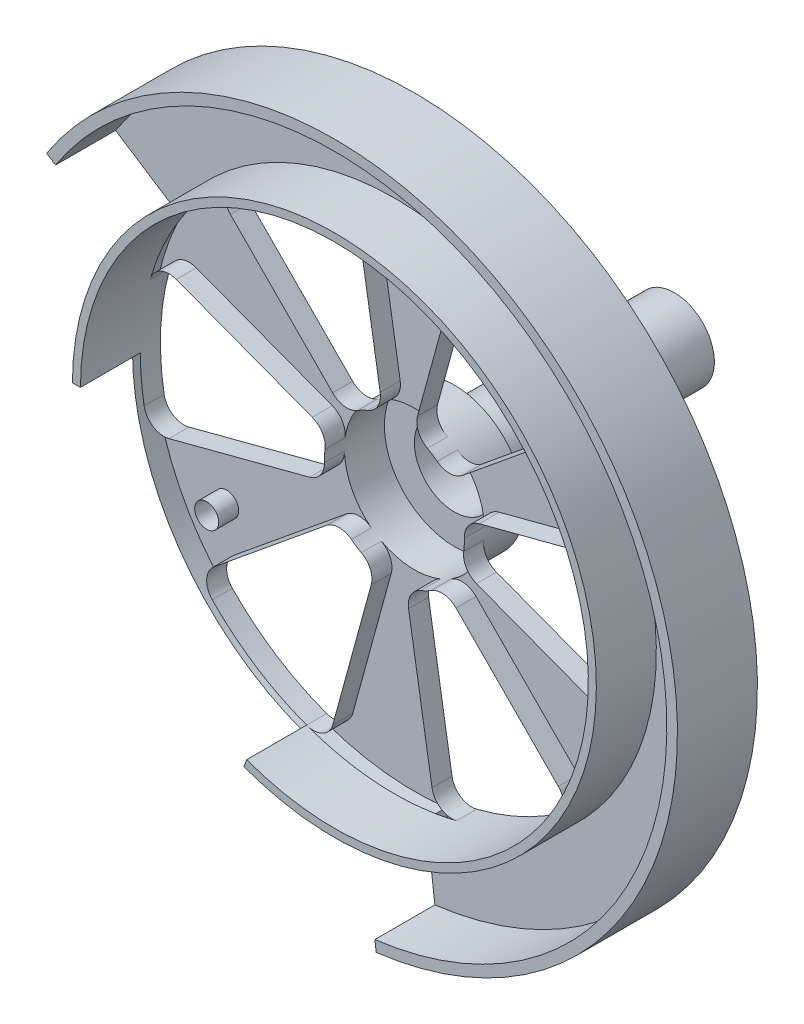
SolidWorks part; units mm, degrees
ref_plane "Piano frontale" through (0, 0, 0) normal (0, 0, 1) x (1, 0, 0)
ref_plane "Piano superiore" through (0, 0, 0) normal (0, 1, 0) x (1, 0, 0)
ref_plane "Piano destro" through (0, 0, 0) normal (1, 0, 0) x (0, 0, -1)
sketch "Schizzo2" plane through (0, 0, 0) normal (0, 0, 1) x (1, 0, 0)
  circle A0 centre (0, 0) radius 65.5
  dimension "D1" = 131
extrude "Estrusione-Estrusione1" add sketch "Schizzo2" along normal blind 5
sketch "Schizzo3" plane through (0, 0, 5) normal (0, 0, 1) x (1, 0, 0)
  line L0 (0, 65.5) -> (0, -65.5) construction
  line L1 (-63.5, 0) -> (0, 0) construction
  line L3 (0, 0) -> (65.5, 0) construction
  line L7 (-3.5452, 21.6491) -> (-9.4192, 57.5198)
  line L8 (-15.4307, 15.5931) -> (-40.998, 41.4296)
  line L9 (-9.4192, 57.5198) -> (0, 0) construction
  line L10 (-40.998, 41.4296) -> (0, 0) construction
  line L11 (5.7887, 21.1599) -> (15.3801, 56.2201)
  line L12 (16.9761, 13.8947) -> (45.104, 36.9172)
  line L13 (21.2194, 5.5668) -> (56.3781, 14.7905)
  line L14 (20.5212, -7.7543) -> (54.5232, -20.6026)
  line L15 (15.4307, -15.5931) -> (40.998, -41.4296)
  line L16 (3.5452, -21.6491) -> (9.4192, -57.5198)
  line L17 (-5.7887, -21.1599) -> (-15.3801, -56.2201)
  line L18 (-16.9761, -13.8947) -> (-45.104, -36.9172)
  line L19 (-21.2194, -5.5668) -> (-56.3781, -14.7905)
  line L20 (-20.5212, 7.7543) -> (-54.5232, 20.6026)
  circle A6 centre (0, 0) radius 65.5 construction
  arc A9 (-6.5951, 16.2097) -> (-9.2374, 14.8634) centre (0, 0) ccw
  arc A11 (-40.998, 41.4296) -> (-40.6444, 48.7882) centre (-37.444, 44.9466) cw
  arc A12 (-15.5803, 61.5589) -> (-9.4192, 57.5198) centre (-14.3535, 56.7118) cw
  arc A13 (-9.2374, 14.8634) -> (-15.4307, 15.5931) centre (-11.8767, 19.1101) cw
  arc A14 (-6.5951, 16.2097) -> (-3.5452, 21.6491) centre (-8.4794, 20.841) ccw
  arc A15 (45.5215, 44.2724) -> (45.104, 36.9172) centre (41.9371, 40.7864) cw
  arc A16 (21.9296, 59.5931) -> (45.5215, 44.2724) centre (0, 0) cw
  arc A17 (15.3801, 56.2201) -> (21.9296, 59.5931) centre (20.2029, 54.9008) cw
  arc A18 (10.7404, 13.8164) -> (8.2534, 15.4315) centre (0, 0) ccw
  arc A19 (8.2534, 15.4315) -> (5.7887, 21.1599) centre (10.6115, 19.8405) cw
  arc A20 (10.7404, 13.8164) -> (16.9761, 13.8947) centre (13.8091, 17.7639) ccw
  arc A21 (61.1018, -17.2865) -> (54.5232, -20.6026) centre (56.2906, -15.9254) cw
  arc A22 (62.574, 10.805) -> (61.1018, -17.2865) centre (0, 0) cw
  arc A23 (56.3781, 14.7905) -> (62.574, 10.805) centre (57.6469, 9.9542) cw
  arc A24 (17.3356, -2.3933) -> (17.4908, 0.5681) centre (0, 0) ccw
  arc A25 (17.4908, 0.5681) -> (21.2194, 5.5668) centre (22.4881, 0.7305) cw
  arc A26 (17.3356, -2.3933) -> (20.5212, -7.7543) centre (22.2886, -3.0771) ccw
  arc A27 (15.5803, -61.5589) -> (9.4192, -57.5198) centre (14.3535, -56.7118) cw
  arc A28 (40.6444, -48.7882) -> (15.5803, -61.5589) centre (0, 0) cw
  arc A29 (40.998, -41.4296) -> (40.6444, -48.7882) centre (37.444, -44.9466) cw
  arc A30 (6.5951, -16.2097) -> (9.2374, -14.8634) centre (0, 0) ccw
  arc A31 (9.2374, -14.8634) -> (15.4307, -15.5931) centre (11.8767, -19.1101) cw
  arc A32 (6.5951, -16.2097) -> (3.5452, -21.6491) centre (8.4794, -20.841) ccw
  arc A33 (-45.5215, -44.2724) -> (-45.104, -36.9172) centre (-41.9371, -40.7864) cw
  arc A34 (-21.9296, -59.5931) -> (-45.5215, -44.2724) centre (0, 0) cw
  arc A35 (-15.3801, -56.2201) -> (-21.9296, -59.5931) centre (-20.2029, -54.9008) cw
  arc A36 (-10.7404, -13.8164) -> (-8.2534, -15.4315) centre (0, 0) ccw
  arc A37 (-8.2534, -15.4315) -> (-5.7887, -21.1599) centre (-10.6115, -19.8405) cw
  arc A38 (-10.7404, -13.8164) -> (-16.9761, -13.8947) centre (-13.8091, -17.7639) ccw
  arc A39 (-61.1018, 17.2865) -> (-54.5232, 20.6026) centre (-56.2906, 15.9254) cw
  arc A40 (-62.574, -10.805) -> (-61.1018, 17.2865) centre (0, 0) cw
  arc A41 (-56.3781, -14.7905) -> (-62.574, -10.805) centre (-57.6469, -9.9542) cw
  arc A42 (-17.3356, 2.3933) -> (-17.4908, -0.5681) centre (0, 0) ccw
  arc A43 (-17.4908, -0.5681) -> (-21.2194, -5.5668) centre (-22.4881, -0.7305) cw
  arc A44 (-17.3356, 2.3933) -> (-20.5212, 7.7543) centre (-22.2886, 3.0771) ccw
  arc A45 (-61.1018, 17.2865) -> (-62.574, -10.805) centre (0, 0) ccw
  arc A46 (-15.5803, 61.5589) -> (-40.6444, 48.7882) centre (0, 0) ccw
  arc A47 (45.5215, 44.2724) -> (21.9296, 59.5931) centre (0, 0) ccw
  arc A48 (61.1018, -17.2865) -> (62.574, 10.805) centre (0, 0) ccw
  arc A49 (15.5803, -61.5589) -> (40.6444, -48.7882) centre (0, 0) ccw
  arc A50 (-45.5215, -44.2724) -> (-21.9296, -59.5931) centre (0, 0) ccw
  dimension "D1" = 35
  dimension "D4" = 5
  dimension "D5" = 5
  dimension "D6" = 5
  dimension "D7" = 5
  dimension "D8" = 6
  dimension "D3" = 35.4
  dimension "D9" = 127
  dimension "D2" = 9.3
extrude "Taglio-Estrusione1" cut sketch "Schizzo3" against normal blind 5 contours A12 A46 A11 L8 A13 A9 A14 L7 | A18 A20 L12 A15 A16 A17 L11 A19 | A24 A26 L14 A21 A22 A23 L13 A25 | A30 A32 L16 A27 A28 A29 L15 A31 | A36 A38 L18 A33 A34 A35 L17 A37 | A42 A44 L20 A39 A40 A41 L19 A43
sketch "Schizzo4" plane through (0, 0, 5) normal (0, 0, 1) x (1, 0, 0)
  line L0 (-65.4996, 0.2321) -> (-63.4996, 0.225)
  line L1 (-21.9296, -59.5931) -> (-22.6203, -61.4701)
  arc A0 (-22.6203, -61.4701) -> (-65.4996, 0.2321) centre (0, 0) ccw
  circle A1 centre (0, 0) radius 65.5 construction
  arc A2 (-21.9296, -59.5931) -> (-63.4996, 0.225) centre (0, 0) ccw
  dimension "D1" = 127
  dimension "D2" = 70
extrude "Estrusione-Estrusione2" add sketch "Schizzo4" along normal blind 15
sketch "Schizzo5" plane through (0, 0, 0) normal (0, 0, 1) x (1, 0, 0)
  line L0 (0, 0) -> (0, 85.78) construction
  line L1 (0, 0) -> (-71.9412, 46.7191) construction
  line L2 (-71.9412, 46.7191) -> (-54.9329, 35.6739)
  line L3 (0, 0) -> (10.454, -85.1406) construction
  line L4 (10.454, -85.1406) -> (7.9824, -65.0118)
  arc A0 (10.454, -85.1406) -> (-71.9412, 46.7191) centre (0, 0) ccw
  arc A1 (7.9824, -65.0118) -> (-54.9329, 35.6739) centre (0, 0) ccw
  arc A2 (-65.4996, 0.2321) -> (-22.6203, -61.4701) centre (0, 0) ccw construction
  dimension "D1" = 171.56
  dimension "D2" = 57
  dimension "D3" = 130
extrude "Estrusione-Estrusione3" add sketch "Schizzo5" along normal blind 5
sketch "Schizzo6" plane through (0, 0, 5) normal (0, 0, 1) x (1, 0, 0)
  line L0 (-71.9412, 46.7191) -> (-69.7145, 45.2731)
  line L1 (10.454, -85.1406) -> (10.1304, -82.5054)
  line L2 (7.9824, -65.0118) -> (10.454, -85.1406) construction
  arc A0 (10.454, -85.1406) -> (-71.9412, 46.7191) centre (0, 0) ccw
  arc A1 (10.1304, -82.5054) -> (-69.7145, 45.2731) centre (0, 0) ccw
  circle A2 centre (0, 0) radius 85.78 construction
  arc A3 (10.454, -85.1406) -> (-71.9412, 46.7191) centre (0, 0) ccw construction
  dimension "D1" = 166.25
extrude "Estrusione-Estrusione4" add sketch "Schizzo6" along normal blind 15
sketch "Schizzo7" plane through (0, 0, 0) normal (0, 0, -1) x (-1, 0, 0)
  circle A0 centre (0, 0) radius 17.5
  dimension "D1" = 35
extrude "Estrusione-Estrusione5" add sketch "Schizzo7" along normal blind 10
sketch "Schizzo8" plane through (0, 0, -10) normal (0, 0, -1) x (-1, 0, 0)
  circle A0 centre (0, 0) radius 10
  dimension "D1" = 20
extrude "Estrusione-Estrusione6" add sketch "Schizzo8" along normal blind 55
sketch "Schizzo9" plane through (0, 0, 5) normal (0, 0, 1) x (1, 0, 0)
  circle A0 centre (0, 0) radius 54 construction
  circle A1 centre (-46.9291, -26.7145) radius 3
  arc A2 (-45.104, -36.9172) -> (-45.5215, -44.2724) centre (-41.9371, -40.7864) ccw construction
  point P5 (-48.8185, -23.0815)
  point P6 (0, 0)
  point P7 (-48.1371, -24.4707)
  point P8 (0, 0)
  point P9 (0, 0)
  point P13 (-46.9291, -40.5031)
  dimension "D1" = 108
  dimension "D2" = 6
extrude "Taglio-Estrusione2" cut sketch "Schizzo9" against normal through all
